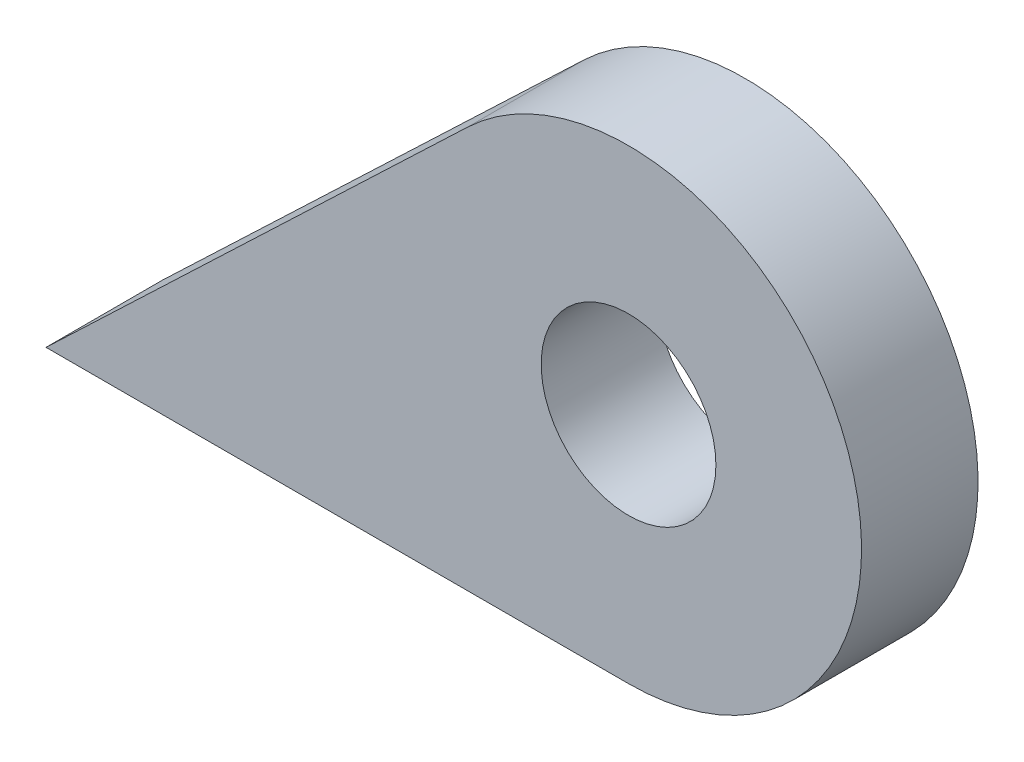
SolidWorks part; units mm, degrees
ref_plane "Front Plane" through (0, 0, 0) normal (0, 0, 1) x (1, 0, 0)
ref_plane "Top Plane" through (0, 0, 0) normal (0, 1, 0) x (1, 0, 0)
ref_plane "Right Plane" through (0, 0, 0) normal (1, 0, 0) x (0, 0, -1)
sketch "Sketch1" plane through (0, 0, 0) normal (0, 0, 1) x (1, 0, 0)
  line L0 (0, -6.35) -> (-15.875, -6.35)
  line L1 (-15.875, -6.35) -> (-4.3793, 4.5983)
  circle A0 centre (0, 0) radius 2.3813
  circle A1 centre (0, 0) radius 6.35
  dimension "D1" = 4.7625
  dimension "D2" = 12.7
  dimension "D3" = 15.875
extrude "Boss-Extrude1" add sketch "Sketch1" along normal blind 3.175 contours A1 L1 L0 | A1 A0
